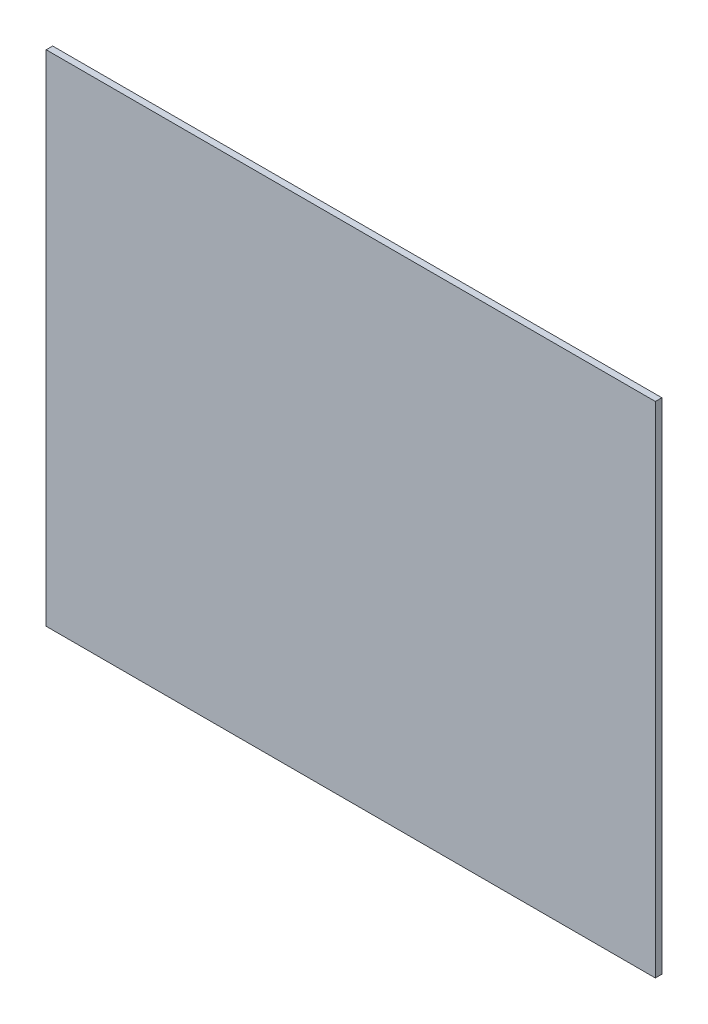
SolidWorks part; units mm, degrees
ref_plane "Front Plane" through (0, 0, 0) normal (0, 0, 1) x (1, 0, 0)
ref_plane "Top Plane" through (0, 0, 0) normal (0, 1, 0) x (1, 0, 0)
ref_plane "Right Plane" through (0, 0, 0) normal (1, 0, 0) x (0, 0, -1)
sketch "Sketch1" plane through (0, 0, 0) normal (0, 0, 1) x (1, 0, 0)
  line L1 (0, 0) -> (61, 0)
  line L2 (0, 0) -> (0, 50)
  line L3 (0, 50) -> (61, 50)
  line L4 (61, 0) -> (61, 50)
  dimension "D1" = 61
  dimension "D2" = 50
extrude "Boss-Extrude1" add sketch "Sketch1" along normal blind 0.65
